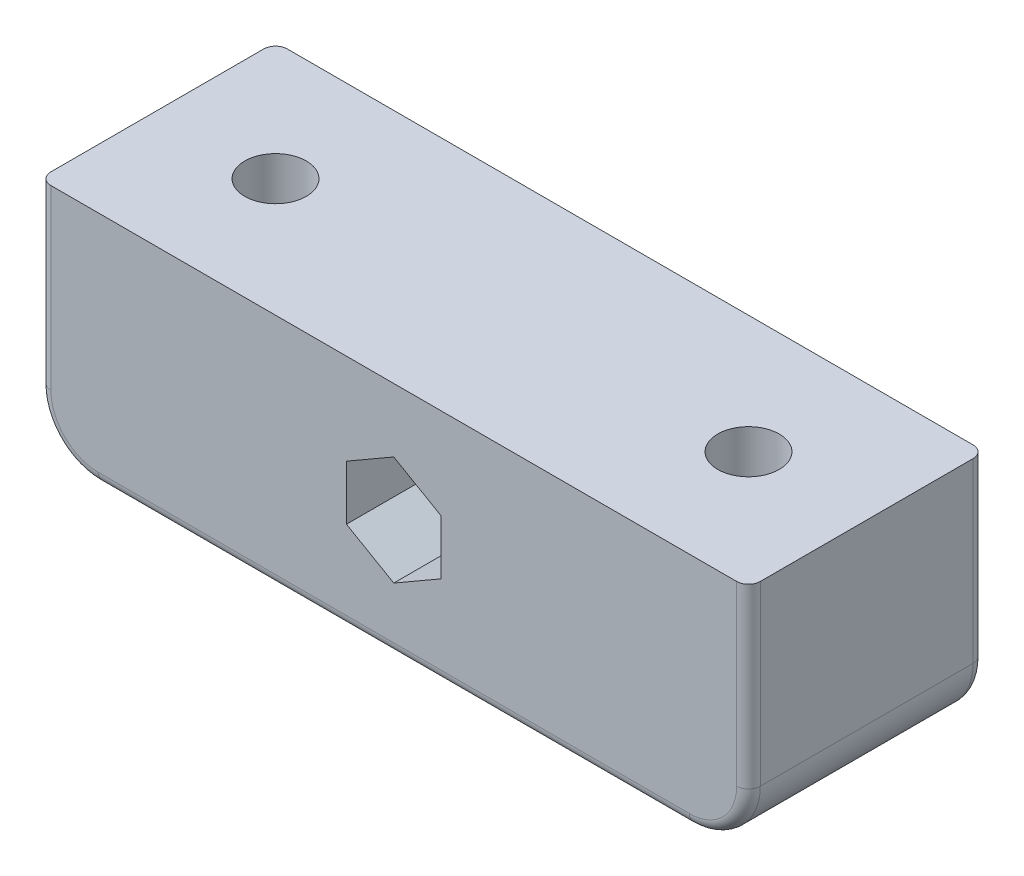
SolidWorks part; units mm, degrees
material "ABS"
ref_plane "Front Plane" through (0, 0, 0) normal (0, 0, 1) x (1, 0, 0)
ref_plane "Top Plane" through (0, 0, 0) normal (0, 1, 0) x (1, 0, 0)
ref_plane "Right Plane" through (0, 0, 0) normal (1, 0, 0) x (0, 0, -1)
sketch "Sketch1" plane through (0, 0, 0) normal (0, 0, 1) x (1, 0, 0)
  line L0 (0, 0) -> (0, -20) construction
  line L1 (-30, 0) -> (30, 0)
  line L2 (-30, 0) -> (-30, -15)
  line L3 (-25, -20) -> (25, -20)
  line L4 (30, 0) -> (30, -15)
  arc A0 (30, -15) -> (25, -20) centre (25, -15) cw
  arc A1 (-25, -20) -> (-30, -15) centre (-25, -15) cw
  circle A2 centre (0, -10) radius 2.6
  point P4 (0, 0)
  point P10 (-30, -20)
  dimension "D3" = 5
  dimension "D4" = 5.2
  dimension "D1" = 20
  dimension "D2" = 60
extrude "Boss-Extrude1" add sketch "Sketch1" along normal blind 20
sketch "Sketch2" plane through (0, 0, 0) normal (0, 1, 0) x (1, 0, 0)
  line L0 (0, 0) -> (0, -20) construction
  line L1 (30, 0) -> (-30, 0) construction
  line L2 (30, -20) -> (-30, -20) construction
  line L3 (0, -10) -> (-30, -10) construction
  line L4 (-30, -20) -> (-30, 0) construction
  circle A0 centre (-20, -10) radius 2.6
  circle A1 centre (20, -10) radius 2.6
  dimension "D1" = 5.2
  dimension "D2" = 20
extrude "Cut-Extrude1" cut sketch "Sketch2" against normal up to surface (20 mm away) up to face at (0, -20, 10)
sketch "Sketch3" plane through (0, 0, 0) normal (0, 0, -1) x (-1, 0, 0)
  line L0 (-30, 0) -> (30, 0) construction
  line L1 (6.0622, -10) -> (3.0311, -4.75)
  line L2 (3.0311, -4.75) -> (-3.0311, -4.75)
  line L3 (-3.0311, -4.75) -> (-6.0622, -10)
  line L4 (-6.0622, -10) -> (-3.0311, -15.25)
  line L5 (-3.0311, -15.25) -> (3.0311, -15.25)
  line L6 (3.0311, -15.25) -> (6.0622, -10)
  circle A0 centre (0, -10) radius 5.25 construction
  dimension "D1" = 10.5
extrude "Cut-Extrude2" cut sketch "Sketch3" against normal blind 3
sketch "Sketch4" plane through (0, 0, 20) normal (0, 0, 1) x (1, 0, 0)
  line L7 (-4, -7.6906) -> (-4, -12.3094)
  line L8 (-4, -12.3094) -> (0, -14.6188)
  line L9 (0, -14.6188) -> (4, -12.3094)
  line L10 (4, -12.3094) -> (4, -7.6906)
  line L11 (4, -7.6906) -> (0, -5.3812)
  line L12 (0, -5.3812) -> (-4, -7.6906)
  line L13 (-30, 0) -> (-30, -15) construction
  circle A0 centre (0, -10) radius 4 construction
  dimension "D1" = 8
extrude "Cut-Extrude3" cut sketch "Sketch4" against normal blind 8
fillet "Fillet1" radius 1 10 edges at (-30, -7.5, 0) (-28.5355, -18.5355, 0) (0, -20, 0) (30, -7.5, 0) (-30, -7.5, 20) (-28.5355, -18.5355, 20) (0, -20, 20) (30, -7.5, 20) (28.5355, -18.5355, 0) (28.5355, -18.5355, 20)
